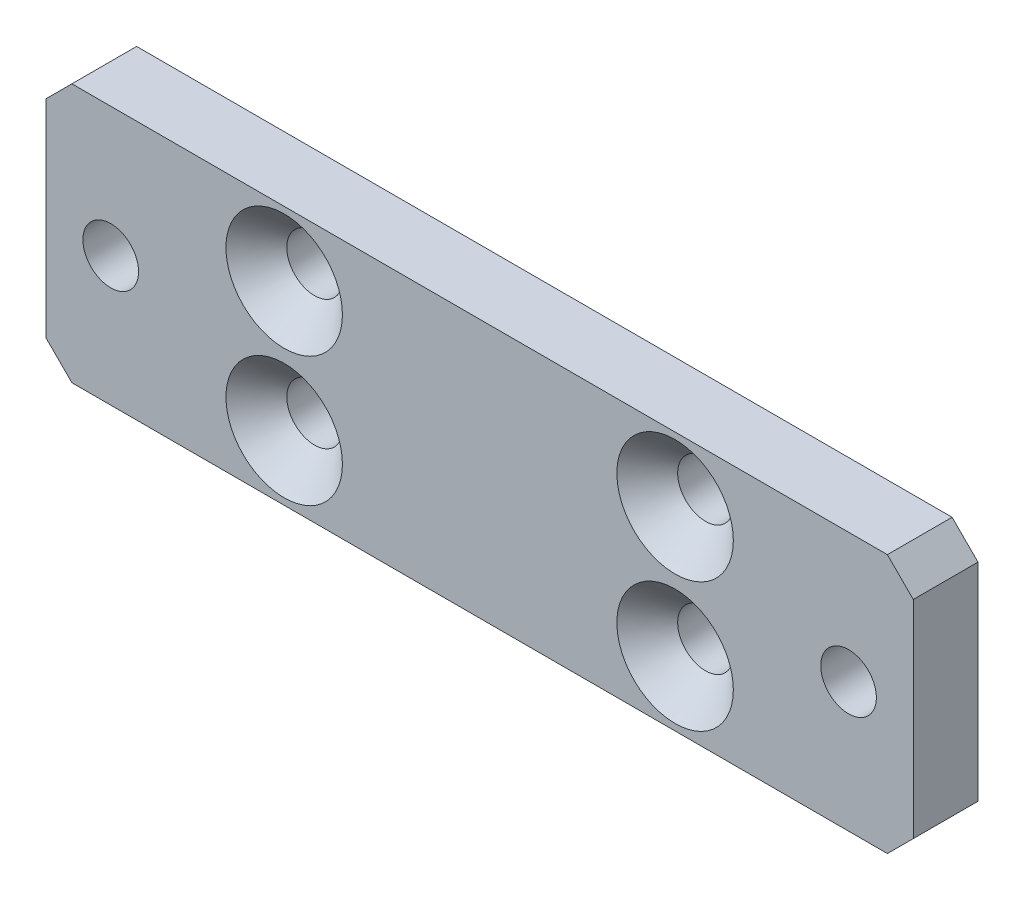
SolidWorks part; units mm, degrees
material "1060 Alloy"
ref_plane "Front Plane" through (0, 0, 0) normal (0, 0, 1) x (1, 0, 0)
ref_plane "Top Plane" through (0, 0, 0) normal (0, 1, 0) x (1, 0, 0)
ref_plane "Right Plane" through (0, 0, 0) normal (1, 0, 0) x (0, 0, -1)
sketch "Sketch1" plane through (0, 0, 0) normal (0, 0, 1) x (1, 0, 0)
  line L1 (33.5, -10) -> (-33.5, -10)
  line L2 (33.5, -10) -> (33.5, 10)
  line L3 (33.5, 10) -> (-33.5, 10)
  line L4 (-33.5, -10) -> (-33.5, 10)
  line L5 (33.5, -10) -> (-33.5, 10) construction
  line L6 (33.5, 10) -> (-33.5, -10) construction
  point P0 (0, 0)
  dimension "D1" = 67
  dimension "D2" = 20
extrude "Boss-Extrude1" add sketch "Sketch1" along normal mid plane 5
hole_wizard "M4 Clearance Hole1" positions "Sketch2" profile "Sketch3" hole size "M4" standard "ISO" end condition through all
sketch "Sketch2" plane through (0, 0, 2.5) normal (0, 0, 1) x (1, 0, 0)
  line L0 (-28.5, 0) -> (28.5, 0) construction
  line L2 (-33.5, 10) -> (-33.5, -10) construction
  point P0 (-28.5, 0)
  point P2 (28.5, 0)
  dimension "D1" = 5
sketch "Sketch3" plane through (-28.5, 0, 2.5) normal (1, 0, 0) x (0, -1, 0)
  line L0 (0, 0) -> (0, 5)
  line L1 (0, 5) -> (2.15, 5)
  line L2 (2.15, 5) -> (2.15, 0)
  line L5 (2.15, 0) -> (0, 0)
  line L11 (0, -6.35) -> (0, 107.95) construction
  dimension "Thru Hole Dia." = 4.3
  dimension "Thru Hole Depth" = 5
hole_wizard "CSK for M4 Hex Socket Countersunk Cap Screw1" positions "Sketch4" profile "Sketch5" countersink size "M4" standard "ISO" end condition through all
sketch "Sketch4" plane through (0, 0, 2.5) normal (0, 0, 1) x (1, 0, 0)
  line L0 (-15.1, -5) -> (15.1, -5) construction
  line L1 (15.1, -5) -> (15.1, 5) construction
  line L2 (15.1, 5) -> (-15.1, 5) construction
  line L3 (-15.1, 5) -> (-15.1, -5) construction
  line L5 (15.1, 5) -> (-15.1, -5) construction
  line L8 (15.1, -11) -> (15.1, 11) construction
  point P0 (-15.1, -5)
  point P2 (-15.1, 5)
  point P4 (15.1, 5)
  point P6 (15.1, -5)
  dimension "D1" = 10
sketch "Sketch5" plane through (-15.1, -5, 2.5) normal (1, 0, 0) x (0, -1, 0)
  line L0 (0, 0) -> (0, 5)
  line L1 (0, 5) -> (2.15, 5)
  line L2 (2.15, 5) -> (2.15, 2.35)
  line L3 (2.15, 2.35) -> (4.5, 0)
  line L5 (4.5, 0) -> (0, 0)
  line L6 (-2.15, 2.35) -> (-4.5, 0) construction
  line L11 (0, -6.35) -> (0, 107.95) construction
  dimension "Thru Hole Dia." = 4.3
  dimension "Thru Hole Depth" = 5
  dimension "Near C'Sink Dia." = 9
  dimension "Near C'Sink Angle" = 90
chamfer "Chamfer1" distance 2 angle 45 4 edges at (-33.5, -10, 0) (33.5, -10, 0) (33.5, 10, 0) (-33.5, 10, 0)
